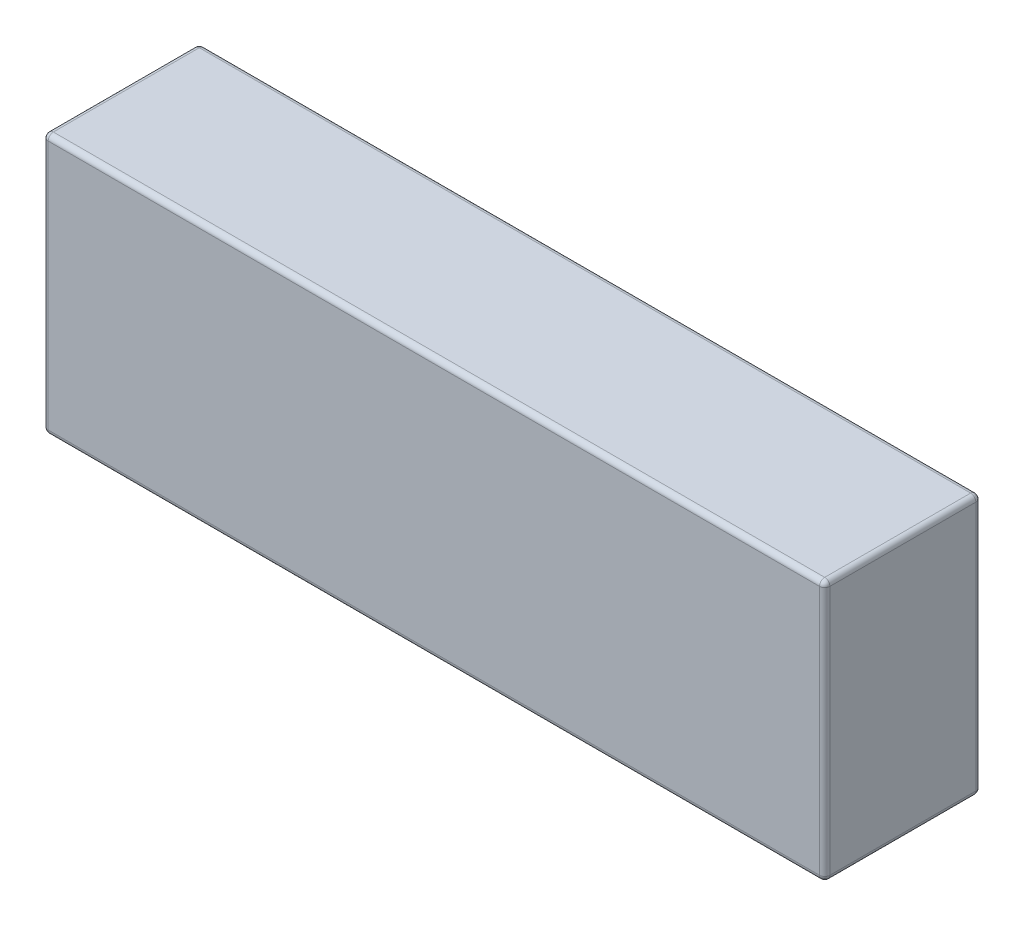
SolidWorks part; units mm, degrees
material "Maple"
ref_plane "Front Plane" through (0, 0, 0) normal (0, 0, 1) x (1, 0, 0)
ref_plane "Top Plane" through (0, 0, 0) normal (0, 1, 0) x (1, 0, 0)
ref_plane "Right Plane" through (0, 0, 0) normal (1, 0, 0) x (0, 0, -1)
sketch "Sketch1" plane through (0, 0, 0) normal (0, 0, 1) x (1, 0, 0)
  line L1 (-75, 25) -> (75, 25)
  line L2 (-75, 25) -> (-75, -25)
  line L3 (-75, -25) -> (75, -25)
  line L4 (75, 25) -> (75, -25)
  line L5 (-75, 25) -> (75, -25) construction
  line L6 (-75, -25) -> (75, 25) construction
  point P0 (0, 0)
  dimension "D1" = 50
  dimension "D2" = 150
extrude "Boss-Extrude1" add sketch "Sketch1" along normal blind 28
sketch "Sketch3" plane through (0, 0, 28) normal (0, 0, 1) x (1, 0, 0)
  line L1 (-75, 25) -> (75, 25)
  line L2 (-75, 25) -> (-75, -25)
  line L3 (-75, -25) -> (75, -25)
  line L4 (75, 25) -> (75, -25)
  line L5 (-75, 25) -> (75, -25) construction
  line L6 (-75, -25) -> (75, 25) construction
  point P0 (0, 0)
extrude "Boss-Extrude2" add sketch "Sketch3" along normal blind 1
sketch "Sketch4" plane through (0, 0, 0) normal (0, 0, -1) x (-1, 0, 0)
  line L1 (-75, 25) -> (75, 25)
  line L2 (-75, 25) -> (-75, -25)
  line L3 (-75, -25) -> (75, -25)
  line L4 (75, 25) -> (75, -25)
  line L5 (-75, 25) -> (75, -25) construction
  line L6 (-75, -25) -> (75, 25) construction
  point P0 (0, 0)
extrude "Boss-Extrude3" add sketch "Sketch4" along normal blind 1
fillet "Fillet1" radius 1 12 edges at (-75, 25, 14) (-75, -25, 14) (75, -25, 14) (0, -25, 29) (-75, 0, 29) (0, -25, -1) (75, 0, -1) (0, 25, -1) (-75, 0, -1) (75, 25, 14) (0, 25, 29) (75, 0, 29)
sketch "Sketch5" plane through (0, 0, -1) normal (0, 0, -1) x (-1, 0, 0)
  line L0 (-92.6765, 14.1347) -> (-92.6765, 169.4681) construction
sketch "Sketch6" plane through (0, 0, 29) normal (0, 0, 1) x (1, 0, 0)
  line L0 (13.3076, 93.2758) -> (166.641, 93.2758) construction
sketch "Sketch7" plane through (0, 0, -1) normal (0, 0, -1) x (-1, 0, 0)
  line L0 (0, 25) -> (0, -25)
  line L1 (-74, 25) -> (74, 25) construction
  line L4 (-25, 25) -> (25, 25)
  line L5 (-25, 25) -> (-25, -25)
  line L6 (-25, -25) -> (25, -25)
  line L7 (25, 25) -> (25, -25)
  line L8 (-25, 25) -> (25, -25) construction
  line L9 (-25, -25) -> (25, 25) construction
  point P4 (0, 0)
  point P6 (0, 0)
  point P11 (0, 0)
  point P12 (0, 0)
  dimension "D1" = 50
